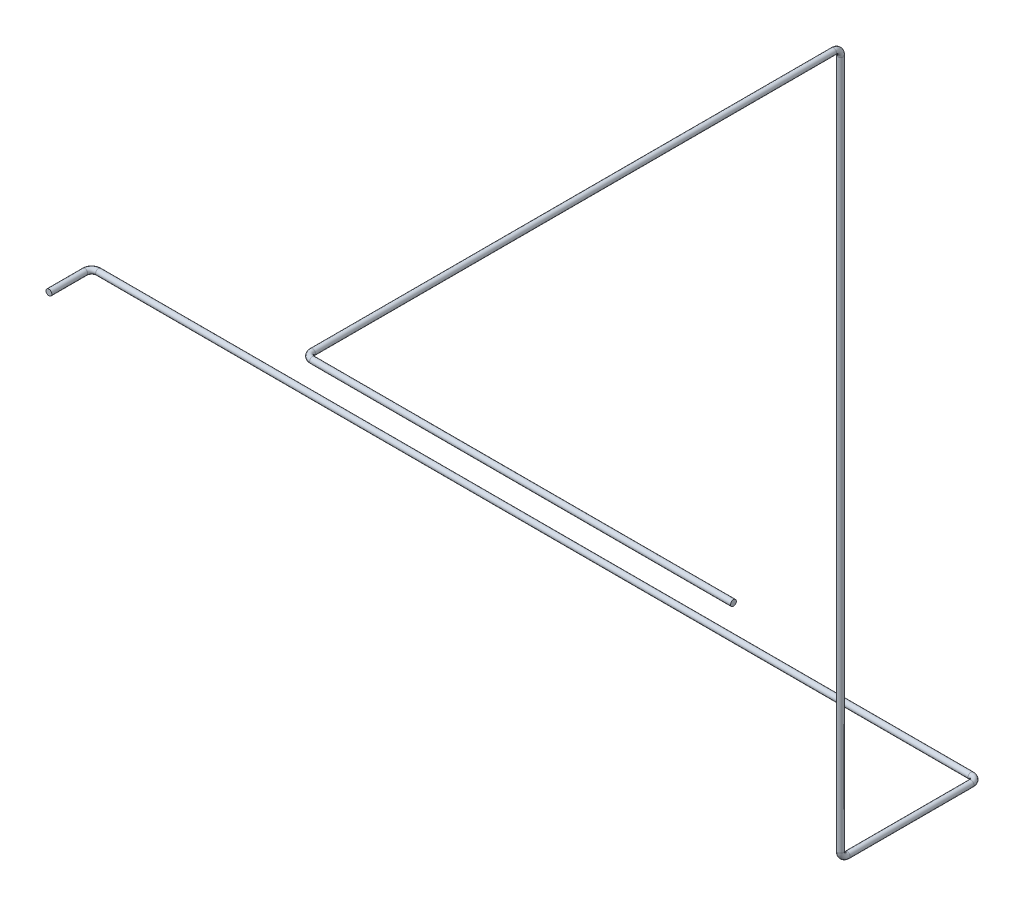
SolidWorks part; units mm, degrees
ref_plane "Alzado" through (0, 0, 0) normal (0, 0, 1) x (1, 0, 0)
ref_plane "Planta" through (0, 0, 0) normal (0, 1, 0) x (1, 0, 0)
ref_plane "Vista lateral" through (0, 0, 0) normal (1, 0, 0) x (0, 0, -1)
sketch "Croquis1" plane through (0, 0, 0) normal (0, 0, 1) x (1, 0, 0)
  circle A0 centre (0, 0) radius 19.05
  dimension "D1" = 38.1
extrude "Saliente-Extruir1" add sketch "Croquis1" along normal blind 200
sketch3d "Croquis3D1"
  line L0 (0, 0, 0) -> (0, 0, -35)
  line L1 (45, 0, -80) -> (5755, 0, -80)
  line L2 (5800, 0, -35) -> (5800, 0, 775)
  line L3 (5800, 45, 820) -> (5800, 4555, 820)
  line L4 (5800, 4600, 865) -> (5800, 4600, 4275)
  line L5 (5845, 4600, 4320) -> (8600, 4600, 4320)
  arc A0 (5800, 4600, 4275) -> (5845, 4600, 4320) centre (5845, 4600, 4275) ccw
  arc A1 (5800, 4555, 820) -> (5800, 4600, 865) centre (5800, 4555, 865) ccw
  arc A2 (5800, 0, 775) -> (5800, 45, 820) centre (5800, 45, 775) ccw
  arc A3 (5755, 0, -80) -> (5800, 0, -35) centre (5755, 0, -35) ccw
  arc A4 (0, 0, -35) -> (45, 0, -80) centre (45, 0, -35) ccw
  point P10 (5800, 4600, 4320)
  point P11 (5845, 4645, 4275)
  point P14 (5800, 4600, 820)
  point P15 (5845, 4555, 865)
  point P18 (5800, 0, 820)
  point P19 (5755, 45, 775)
  point P22 (5800, 0, -80)
  point P23 (5755, -45, -35)
  point P26 (0, 0, -80)
  point P27 (45, -45, -35)
  dimension "D7" = 45
  dimension "D1" = 80
  dimension "D2" = 5800
  dimension "D3" = 900
  dimension "D4" = 4600
  dimension "D5" = 3500
  dimension "D6" = 2800
sketch "Croquis2" plane through (0, 0, 0) normal (0, 0, -1) x (-1, 0, 0)
  circle A0 centre (0, 0) radius 19.05
sweep "Barrer1" add profiles "Croquis2" path "Croquis3D1"
